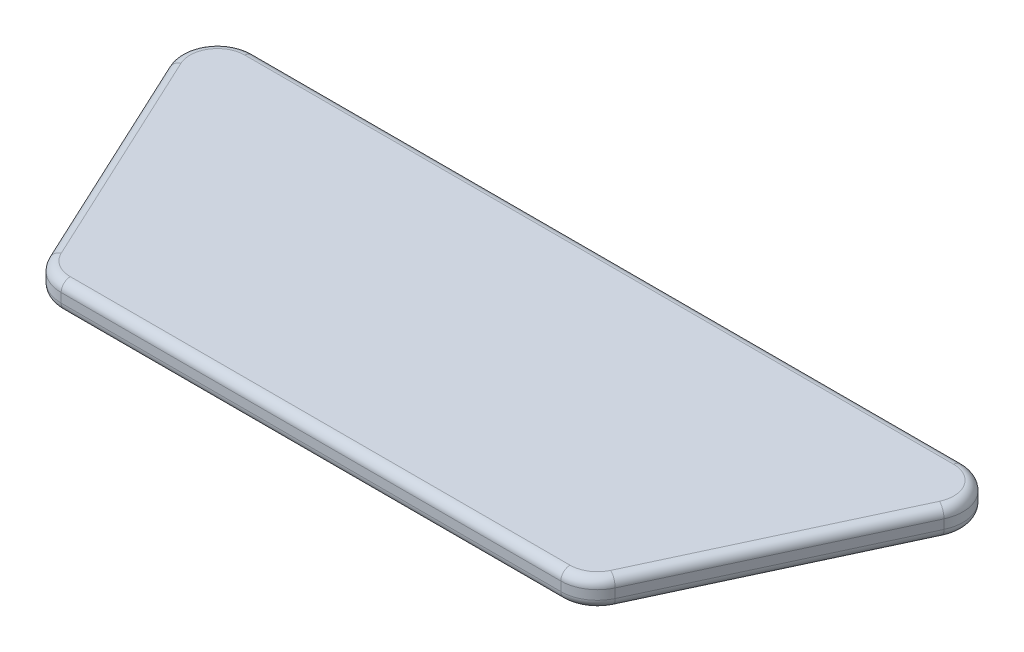
SolidWorks part; units mm, degrees
ref_plane "Front Plane" through (0, 0, 0) normal (0, 0, 1) x (1, 0, 0)
ref_plane "Top Plane" through (0, 0, 0) normal (0, 1, 0) x (1, 0, 0)
ref_plane "Right Plane" through (0, 0, 0) normal (1, 0, 0) x (0, 0, -1)
sketch "Sketch1" plane through (0, 0, 0) normal (0, 1, 0) x (1, 0, 0)
  line L0 (15.948, 0) -> (212.652, 0)
  line L1 (221.8601, -14.4538) -> (192.8418, -76.6838)
  line L2 (183.6337, -82.55) -> (44.9663, -82.55)
  line L3 (35.7582, -76.6838) -> (6.7399, -14.4538)
  arc A0 (212.652, 0) -> (221.8601, -14.4538) centre (212.652, -10.16) cw
  arc A1 (192.8418, -76.6838) -> (183.6337, -82.55) centre (183.6337, -72.39) cw
  arc A2 (44.9663, -82.55) -> (35.7582, -76.6838) centre (44.9663, -72.39) cw
  arc A3 (15.948, 0) -> (6.7399, -14.4538) centre (15.948, -10.16) ccw
  point P7 (228.6, 0)
  point P14 (0, 0)
  dimension "D4" = 10.16
  dimension "D1" = 82.55
  dimension "D2" = 228.6
  dimension "D3" = 115
extrude "Boss-Extrude1" add sketch "Sketch1" along normal blind 7.62
fillet "Fillet1" radius 2.54 16 edges at (39.5074, 0, 80.9589) (21.2491, 0, 45.5688) (7.3791, 0, 4.701) (114.3, 0, 0) (221.2209, 0, 4.701) (207.3509, 0, 45.5688) (189.0926, 0, 80.9589) (39.5074, 7.62, 80.9589) (21.2491, 7.62, 45.5688) (7.3791, 7.62, 4.701) (114.3, 7.62, 0) (221.2209, 7.62, 4.701) (207.3509, 7.62, 45.5688) (189.0926, 7.62, 80.9589) (114.3, 0, 82.55) (114.3, 7.62, 82.55)
sketch "Sketch2" plane through (0, 0, 0) normal (0, -1, 0) x (1, 0, 0)
  line L0 (114.3, 0) -> (114.3, 82.55) construction
  line L1 (212.652, 0) -> (15.948, 0) construction
  line L2 (44.9663, 82.55) -> (183.6337, 82.55) construction
  line L3 (21.2491, 45.5688) -> (207.3509, 45.5688) construction
  line L4 (6.7399, 14.4538) -> (35.7582, 76.6838) construction
  line L5 (192.8418, 76.6838) -> (221.8601, 14.4538) construction
  line L6 (52.0303, 61.9125) -> (60.2853, 70.1675) construction
  line L11 (30.3144, 11.1125) -> (38.5694, 19.3675) construction
  line L12 (30.3144, 19.3675) -> (38.5694, 11.1125) construction
  line L13 (52.0303, 70.1675) -> (60.2853, 61.9125) construction
  line L14 (183.6337, 80.01) -> (44.9663, 80.01) construction
  line L15 (176.5697, 70.1675) -> (168.3147, 61.9125) construction
  line L16 (176.5697, 61.9125) -> (168.3147, 70.1675) construction
  line L17 (198.2856, 19.3675) -> (190.0306, 11.1125) construction
  line L18 (198.2856, 11.1125) -> (190.0306, 19.3675) construction
  circle A0 centre (30.3144, 11.1125) radius 1.27
  circle A1 centre (30.3144, 19.3675) radius 1.27
  circle A2 centre (38.5694, 11.1125) radius 1.27
  circle A3 centre (38.5694, 19.3675) radius 1.27
  circle A4 centre (52.0303, 61.9125) radius 1.27
  circle A5 centre (52.0303, 70.1675) radius 1.27
  circle A6 centre (60.2853, 61.9125) radius 1.27
  circle A7 centre (60.2853, 70.1675) radius 1.27
  circle A8 centre (168.3147, 70.1675) radius 1.27
  circle A9 centre (168.3147, 61.9125) radius 1.27
  circle A10 centre (176.5697, 70.1675) radius 1.27
  circle A11 centre (176.5697, 61.9125) radius 1.27
  circle A12 centre (190.0306, 19.3675) radius 1.27
  circle A13 centre (190.0306, 11.1125) radius 1.27
  circle A14 centre (198.2856, 19.3675) radius 1.27
  circle A15 centre (198.2856, 11.1125) radius 1.27
  point P12 (34.4419, 15.24)
  point P30 (56.1578, 66.04)
  point P42 (172.4422, 66.04)
  point P51 (194.1581, 15.24)
  dimension "D1" = 2.54
  dimension "D2" = 8.255
  dimension "D6" = 2.54
  dimension "D3" = 8.255
  dimension "D4" = 15.24
  dimension "D5" = 25.4
  dimension "D7" = 8.255
  dimension "D8" = 8.255
  dimension "D9" = 13.97
  dimension "D10" = 13.97
scale "Scale1" bodies to scale 102 scale about centroid uniform scaling yes scale factor 1.5
